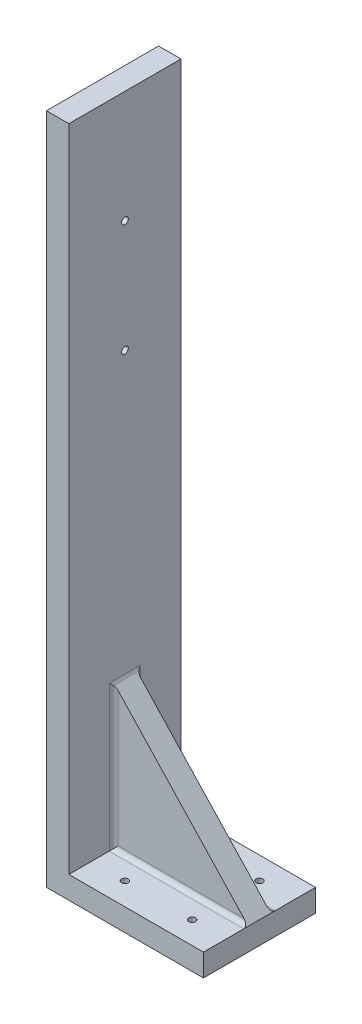
SolidWorks part; units mm, degrees
ref_plane "Front Plane" through (0, 0, 0) normal (0, 0, 1) x (1, 0, 0)
ref_plane "Top Plane" through (0, 0, 0) normal (0, 1, 0) x (1, 0, 0)
ref_plane "Right Plane" through (0, 0, 0) normal (1, 0, 0) x (0, 0, -1)
sketch "Sketch1" plane through (0, 0, 0) normal (0, 0, 1) x (1, 0, 0)
  line L0 (0, 92.0312) -> (0, -107.6562) construction
  line L1 (0, 76.7187) -> (-10, 76.7187)
  line L2 (-10, 76.7187) -> (-10, -223.2813)
  line L3 (-10, -223.2813) -> (60, -223.2813)
  line L4 (60, -223.2813) -> (60, -213.2813)
  line L5 (60, -213.2813) -> (0, -213.2813)
  line L6 (0, -213.2813) -> (0, 76.7187)
  dimension "D1" = 10
  dimension "D2" = 300
  dimension "D3" = 10
  dimension "D4" = 70
extrude "Boss-Extrude1" add sketch "Sketch1" along normal mid plane 50
sketch "Sketch2" plane through (0, 0, 0) normal (1, 0, 0) x (0, 0, -1)
  line L0 (-25, -213.2813) -> (25, -213.2813) construction
  line L1 (-5, -213.2813) -> (5, -213.2813)
  line L2 (-5, -213.2813) -> (-5, -149.1766)
  line L3 (-5, -149.1766) -> (5, -149.1766)
  line L4 (5, -213.2813) -> (5, -149.1766)
  line L5 (0, -213.2813) -> (0, -131.9187) construction
  line L6 (25, -213.2813) -> (25, 76.7187) construction
  dimension "D1" = 5
  dimension "D2" = 20
extrude "Boss-Extrude2" add sketch "Sketch2" along normal blind 60
sketch "Sketch3" plane through (0, 0, 5) normal (0, 0, 1) x (1, 0, 0)
  line L0 (0, -149.1766) -> (60, -213.2813)
  line L1 (60, -213.2813) -> (60, -149.1766)
  line L2 (60, -149.1766) -> (0, -149.1766)
extrude "Cut-Extrude1" cut sketch "Sketch3" against normal blind 60
sketch "Sketch4" plane through (0, -213.2813, 0) normal (0, 1, 0) x (1, 0, 0)
  line L0 (0, 15) -> (60, 15) construction
  line L1 (0, 5) -> (0, 25) construction
  line L2 (60, 5) -> (60, 25) construction
  line L3 (60, 15) -> (60, -15) construction
  line L4 (60, -25) -> (60, -5) construction
  line L5 (60, -15) -> (0, -15) construction
  line L6 (0, -25) -> (0, -5) construction
  line L7 (30, -25) -> (30, 25) construction
  line L8 (60, -25) -> (0, -25) construction
  line L9 (60, 25) -> (0, 25) construction
  circle A0 centre (15, 15) radius 1.5
  circle A1 centre (15, -15) radius 1.5
  circle A2 centre (45, -15) radius 1.5
  circle A3 centre (45, 15) radius 1.5
  dimension "D1" = 3
  dimension "D3" = 3
  dimension "D2" = 15
  dimension "D4" = 15
extrude "Cut-Extrude2" cut sketch "Sketch4" against normal blind 60
fillet "Fillet1" radius 2 5 edges at (0, -149.1766, 0) (30, -213.2813, -5) (0, -181.2289, -5) (30, -213.2813, 5) (0, -181.2289, 5)
sketch "Sketch13" plane through (0, 0, 0) normal (1, 0, 0) x (0, 0, -1)
  line L0 (0, 76.7187) -> (0, -213.2813) construction
  line L1 (-25, 76.7187) -> (25, 76.7187) construction
  line L2 (7, -213.2813) -> (-7, -213.2813) construction
  circle A0 centre (0, 26.7187) radius 1.5
  circle A1 centre (0, -23.2813) radius 1.5
  dimension "D1" = 3
  dimension "D2" = 3
  dimension "D3" = 50
  dimension "D4" = 50
extrude "Cut-Extrude3" cut sketch "Sketch13" against normal blind 10
